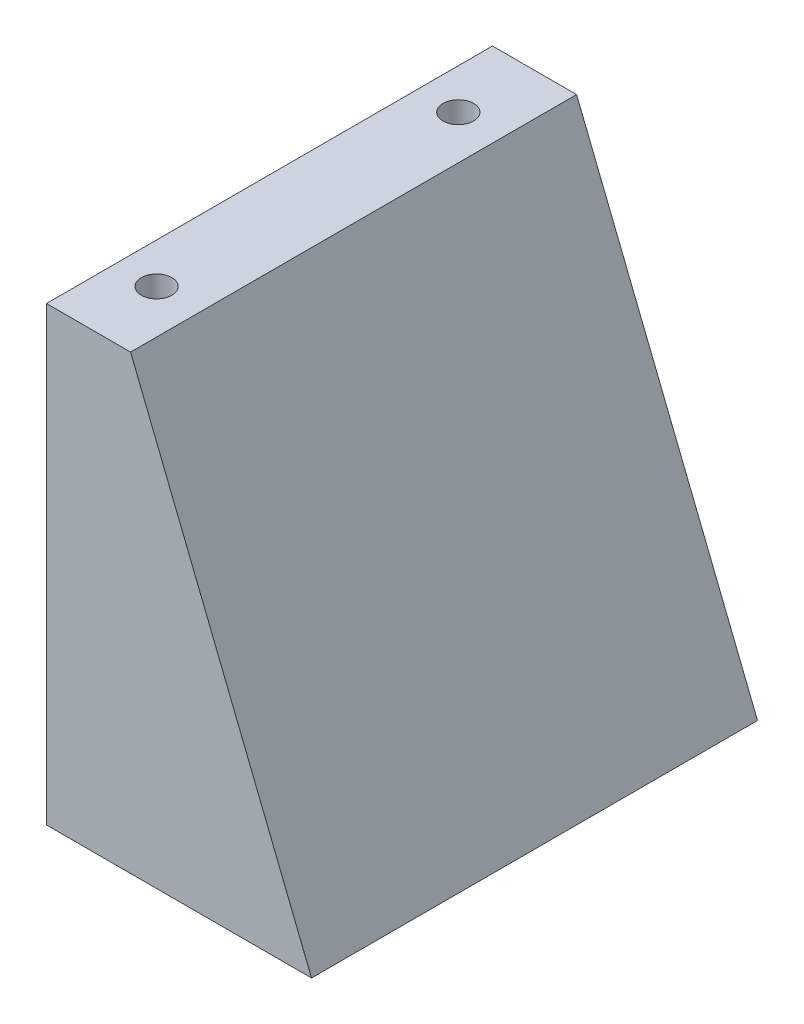
SolidWorks part; units mm, degrees
ref_plane "Front Plane" through (0, 0, 0) normal (0, 0, 1) x (1, 0, 0)
ref_plane "Top Plane" through (0, 0, 0) normal (0, 1, 0) x (1, 0, 0)
ref_plane "Right Plane" through (0, 0, 0) normal (1, 0, 0) x (0, 0, -1)
sketch "Sketch1" plane through (0, 0, 0) normal (0, 0, 1) x (1, 0, 0)
  line L0 (0, 0) -> (0, 44.3)
  line L1 (0, 0) -> (26, 0)
  line L2 (26, 0) -> (8.25, 44.3)
  line L3 (8.25, 44.3) -> (0, 44.3)
  dimension "D1" = 44.3
  dimension "D2" = 26
  dimension "D3" = 8.25
extrude "Boss-Extrude1" add sketch "Sketch1" along normal blind 43.75
sketch "Sketch2" plane through (0, 0, 0) normal (-1, 0, 0) x (0, 0, 1)
  line L0 (21.875, 44.3) -> (21.875, 37.4482) construction
  line L1 (43.75, 44.3) -> (0, 44.3) construction
  line L2 (0, 22.15) -> (4.141, 22.15) construction
  line L3 (0, 44.3) -> (0, 0) construction
  circle A0 centre (5.875, 38.15) radius 1.6
  circle A1 centre (37.875, 38.15) radius 1.6
  circle A2 centre (5.875, 6.15) radius 1.6
  circle A3 centre (37.875, 6.15) radius 1.6
  dimension "D1" = 3.2
  dimension "D2" = 32
  dimension "D3" = 32
  dimension "D4" = 16
  dimension "D5" = 16
extrude "Cut-Extrude1" cut sketch "Sketch2" against normal blind 3
sketch "Sketch3" plane through (0, 44.3, 0) normal (0, 1, 0) x (1, 0, 0)
  line L1 (3.95, -7.3) -> (3.95, -5.8) construction
  line L2 (8.25, 0) -> (0, 0) construction
  line L3 (3.95, -7.3) -> (2.45, -7.3) construction
  line L4 (0, -43.75) -> (0, 0) construction
  circle A0 centre (3.95, -7.3) radius 1.5
  circle A1 centre (3.95, -36.9) radius 1.5
  dimension "D3" = 3
  dimension "D1" = 29.6
  dimension "D2" = 5.8
  dimension "D4" = 2.45
extrude "Cut-Extrude2" cut sketch "Sketch3" against normal blind 3
